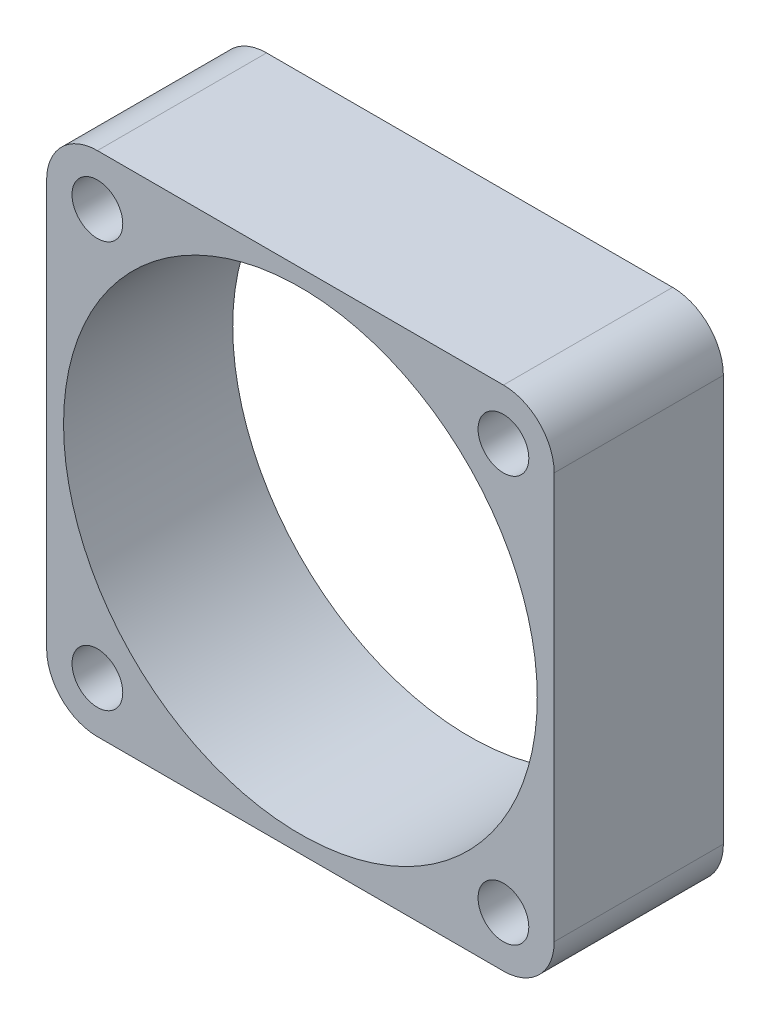
SolidWorks part; units mm, degrees
ref_plane "前视基准面" through (0, 0, 0) normal (0, 0, 1) x (1, 0, 0)
ref_plane "上视基准面" through (0, 0, 0) normal (0, 1, 0) x (1, 0, 0)
ref_plane "右视基准面" through (0, 0, 0) normal (1, 0, 0) x (0, 0, -1)
sketch "草图1" plane through (0, 0, 0) normal (0, 0, 1) x (1, 0, 0)
  line L1 (15, 15) -> (-15, 15)
  line L2 (15, 15) -> (15, -15)
  line L3 (15, -15) -> (-15, -15)
  line L4 (-15, 15) -> (-15, -15)
  line L5 (15, 15) -> (-15, -15) construction
  line L6 (15, -15) -> (-15, 15) construction
  circle A0 centre (0, 0) radius 14
  circle A1 centre (-12, 12) radius 1.5
  circle A2 centre (12, 12) radius 1.5
  circle A3 centre (12, -12) radius 1.5
  circle A4 centre (-12, -12) radius 1.5
  point P0 (0, 0)
  point P19 (0, 0)
  dimension "D3" = 3
  dimension "D1" = 30
  dimension "D2" = 30
  dimension "D4" = 4
extrude "凸台-拉伸1" add sketch "草图1" along normal blind 10
fillet "圆角1" radius 3 4 edges at (-15, -15, 5) (-15, 15, 5) (15, -15, 5) (15, 15, 5)
